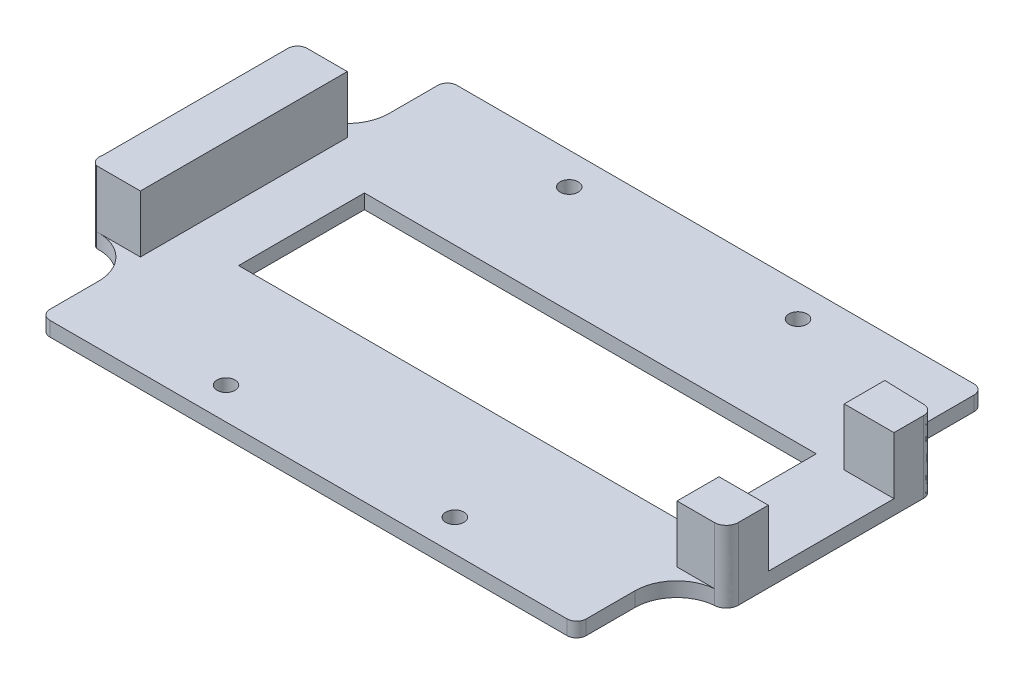
SolidWorks part; units mm, degrees
ref_plane "Front Plane" through (0, 0, 0) normal (0, 0, 1) x (1, 0, 0)
ref_plane "Top Plane" through (0, 0, 0) normal (0, 1, 0) x (1, 0, 0)
ref_plane "Right Plane" through (0, 0, 0) normal (1, 0, 0) x (0, 0, -1)
sketch "Sketch1" plane through (0, -197.5463, 0) normal (0, 1, 0) x (1, 0, 0)
  line L2 (-46.8784, -25.6022) -> (-46.8784, -34.1022)
  line L6 (46.8784, -34.1022) -> (46.8784, -25.6022)
  line L9 (46.8784, 25.1978) -> (46.8784, 33.6978)
  line L13 (-46.8784, 33.6978) -> (-46.8784, 25.1978)
  line L14 (-45.2, -35.7807) -> (45.2, -35.7807)
  line L15 (-55.5784, -16.2029) -> (-55.5784, 16.2029)
  line L16 (-45.2, 35.3762) -> (45.2, 35.3762)
  line L17 (55.5784, 16.2029) -> (55.5784, -16.2029)
  line L18 (-55.5784, 0) -> (55.5784, 0) construction
  line L19 (0, 35.3762) -> (0, -35.7807) construction
  line L21 (42, -11) -> (-37, -11)
  line L22 (42, -11) -> (42, 11)
  line L23 (42, 11) -> (-37, 11)
  line L24 (-37, -11) -> (-37, 11)
  arc A0 (-46.8784, -25.6022) -> (-54.5309, -18.2881) centre (-54.2, -25.6022) ccw
  arc A1 (-46.8784, -34.1022) -> (-45.2, -35.7807) centre (-45.2, -34.1022) ccw
  arc A2 (45.2, -35.7807) -> (46.8784, -34.1022) centre (45.2, -34.1022) ccw
  arc A3 (53.5399, -18.3105) -> (46.8784, -25.6022) centre (54.2, -25.6022) ccw
  arc A4 (46.8784, 25.1978) -> (53.956, 17.8802) centre (54.2, 25.1978) ccw
  arc A5 (46.8784, 33.6978) -> (45.2, 35.3762) centre (45.2, 33.6978) ccw
  arc A6 (-45.2, 35.3762) -> (-46.8784, 33.6978) centre (-45.2, 33.6978) ccw
  arc A7 (-53.956, 17.8802) -> (-46.8784, 25.1978) centre (-54.2, 25.1978) ccw
  circle A8 centre (-20, 29.7978) radius 1.5784
  circle A9 centre (-20, -30.2022) radius 1.5784
  circle A10 centre (20, -30.2022) radius 1.5784
  circle A11 centre (20, 29.7978) radius 1.5784
  spline S12 degree 3 poles (-55.5784, -16.2029) (-55.6424, -16.4073) (-55.6912, -16.8461) (-55.5132, -17.4763) (-55.1127, -17.996) (-54.7326, -18.2176) (-54.5309, -18.2881) knots 0 0 0 0 0.001024 0.002047 0.003071 0.004095 0.004095 0.004095 0.004095
  spline S13 degree 3 poles (53.5399, -18.3105) (53.8088, -18.3015) (54.3495, -18.1774) (55.0231, -17.7048) (55.4733, -17.0142) (55.5784, -16.4714) (55.5784, -16.2029) knots 0 0 0 0 0.001024 0.002047 0.003071 0.004095 0.004095 0.004095 0.004095
  spline S14 degree 3 poles (55.5784, 16.2029) (55.5784, 16.417) (55.494, 16.8504) (55.136, 17.3987) (54.5986, 17.7752) (54.1696, 17.8731) (53.956, 17.8802) knots 0 0 0 0 0.001024 0.002047 0.003071 0.004095 0.004095 0.004095 0.004095
  spline S15 degree 3 poles (-53.956, 17.8802) (-54.1701, 17.8731) (-54.6004, 17.7743) (-55.1365, 17.3982) (-55.4948, 16.8485) (-55.5784, 16.4166) (-55.5784, 16.2029) knots 0 0 0 0 0.001024 0.002047 0.003071 0.004095 0.004095 0.004095 0.004095
  point P4 (0, 0)
  point P9 (0, 0)
  dimension "D11" = 7.3216
  dimension "D14" = 7.3216
  dimension "D16" = 1.6784
  dimension "D18" = 7.3216
  dimension "D19" = 7.3216
  dimension "D22" = 3.1568
  dimension "D13" = 1.6784
  dimension "D27" = 7.3175
  dimension "D46" = 54.2
  dimension "D47" = 33.6978
  dimension "D51" = 30.2022
  dimension "D52" = 30.2022
  dimension "D53" = 20
  dimension "D54" = 20
  dimension "D56" = 29.7978
  dimension "D3" = 5.5784
  dimension "D4" = 5.5784
  dimension "D5" = 40
  dimension "D6" = 5.5784
  dimension "D7" = 5.5784
  dimension "D8" = 93.7568
  dimension "D9" = 40
  dimension "D10" = 60
  dimension "D12" = 60
  dimension "D15" = 26.8784
  dimension "D17" = 26.8784
  dimension "D20" = 1.6784
  dimension "D21" = 8.5
  dimension "D23" = 7.3141
  dimension "D24" = 2.0853
  dimension "D25" = 32.4057
  dimension "D26" = 1.6774
  dimension "D28" = 8.5
  dimension "D29" = 1.6784
  dimension "D30" = 90.4
  dimension "D31" = 1.6784
  dimension "D32" = 1.6784
  dimension "D33" = 93.7568
  dimension "D34" = 1.6784
  dimension "D35" = 8.5
  dimension "D36" = 7.3175
  dimension "D37" = 1.6774
  dimension "D38" = 32.4057
  dimension "D39" = 2.1076
  dimension "D40" = 7.2918
  dimension "D41" = 8.5
  dimension "D42" = 1.6784
  dimension "D43" = 90.4
  dimension "D44" = 1.6784
  dimension "D45" = 35.7807
  dimension "D48" = 18.2881
  dimension "D49" = 55.5784
  dimension "D50" = 1.6784
  dimension "D55" = 29.7978
  dimension "D57" = 20
  dimension "D58" = 35.3762
  dimension "D59" = 55.5784
  dimension "D60" = 35.7807
  dimension "D61" = 11
  dimension "D62" = 11
  dimension "D63" = 42
  dimension "D64" = 37
extrude "Boss-Extrude2" add sketch "Sketch1" along normal blind 2.54
sketch "Sketch2" plane through (0, -195.0063, 0) normal (0, 1, 0) x (1, 0, 0)
  line L0 (-55.5784, 16.2029) -> (-55.5784, -16.2029) construction
  line L1 (-55.5784, 16.2029) -> (-55.5784, -16.2029)
  line L6 (55.5784, -10.9741) -> (46.9607, -10.9741)
  line L7 (55.5784, -16.2029) -> (55.5784, -10.9741)
  line L8 (55.5784, 10.9995) -> (46.8784, 10.9995)
  line L9 (46.8784, 10.9995) -> (46.8784, 18.0987)
  line L10 (46.9607, -10.9741) -> (46.9607, -18.3105)
  line L11 (55.5784, 16.2029) -> (55.5784, 10.9995)
  line L12 (53.5399, -18.3105) -> (46.9607, -18.3105)
  line L13 (53.956, 17.8802) -> (46.8784, 18.0987)
  line L14 (-54.5309, -18.2881) -> (-46.8784, -18.2881)
  line L15 (-46.8784, 17.8802) -> (-53.956, 17.8802)
  line L16 (-46.8784, 17.8802) -> (-46.8784, -18.2881)
  spline S0 degree 3 poles (-2887.2621, -961.4357) (19.4846, -83.0265) (-45.1569, 24.4001) (-55.1365, 17.3982) (-61.9111, 7.0053) (51.9441, -54.0774) (771.7464, 2897.4151) knots -0.0541 -0.0541 -0.0541 -0.0541 0.001024 0.002047 0.003071 0.059094 0.059094 0.059094 0.059094 only from (-53.956, 17.8802) to (-55.5784, 16.2029) construction
  spline S1 degree 3 poles (-66.8096, -3013.9578) (63.9193, 19.7967) (-58.8269, -5.7444) (-55.5132, -17.4763) (-47.9405, -27.3028) (47.3128, 59.9949) (-2500.9183, 1714.0565) knots -0.0541 -0.0541 -0.0541 -0.0541 0.001024 0.002047 0.003071 0.059094 0.059094 0.059094 0.059094 only from (-55.5784, -16.2029) to (-54.5309, -18.2881) construction
  spline S2 degree 3 poles (-53.956, 17.8802) (-54.1701, 17.8731) (-54.6004, 17.7743) (-55.1365, 17.3982) (-55.4948, 16.8485) (-55.5784, 16.4166) (-55.5784, 16.2029) knots 0 0 0 0 0.001024 0.002047 0.003071 0.004095 0.004095 0.004095 0.004095
  spline S3 degree 3 poles (-55.5784, -16.2029) (-55.6424, -16.4073) (-55.6912, -16.8461) (-55.5132, -17.4763) (-55.1127, -17.996) (-54.7326, -18.2176) (-54.5309, -18.2881) knots 0 0 0 0 0.001024 0.002047 0.003071 0.004095 0.004095 0.004095 0.004095
  spline S4 degree 3 poles (-828.7849, 2880.5674) (-47.7194, -53.8347) (61.8015, 7.1914) (55.136, 17.3987) (44.9746, 24.5159) (-19.868, -87.2408) (2906.001, -904.9902) knots -0.0541 -0.0541 -0.0541 -0.0541 0.001024 0.002047 0.003071 0.059094 0.059094 0.059094 0.059094 only from (55.5784, 16.2029) to (53.956, 17.8802) construction
  spline S5 degree 3 poles (2877.192, 987.317) (-27.534, 90.0061) (43.3597, -25.8882) (55.0231, -17.7048) (62.9408, -5.5584) (-59.9446, 61.5126) (-799.2802, -2888.9508) knots -0.050107 -0.050107 -0.050107 -0.050107 0.001024 0.002047 0.003071 0.055038 0.055038 0.055038 0.055038 only from (53.5399, -18.3105) to (55.5784, -16.2029) construction
  spline S6 degree 3 poles (55.5784, 16.2029) (55.5784, 16.417) (55.494, 16.8504) (55.136, 17.3987) (54.5986, 17.7752) (54.1696, 17.8731) (53.956, 17.8802) knots 0 0 0 0 0.001024 0.002047 0.003071 0.004095 0.004095 0.004095 0.004095
  spline S7 degree 3 poles (53.5399, -18.3105) (53.8088, -18.3015) (54.3495, -18.1774) (55.0231, -17.7048) (55.4733, -17.0142) (55.5784, -16.4714) (55.5784, -16.2029) knots 0 0 0 0 0.001024 0.002047 0.003071 0.004095 0.004095 0.004095 0.004095
extrude "Boss-Extrude3" add sketch "Sketch2" along normal blind 10
